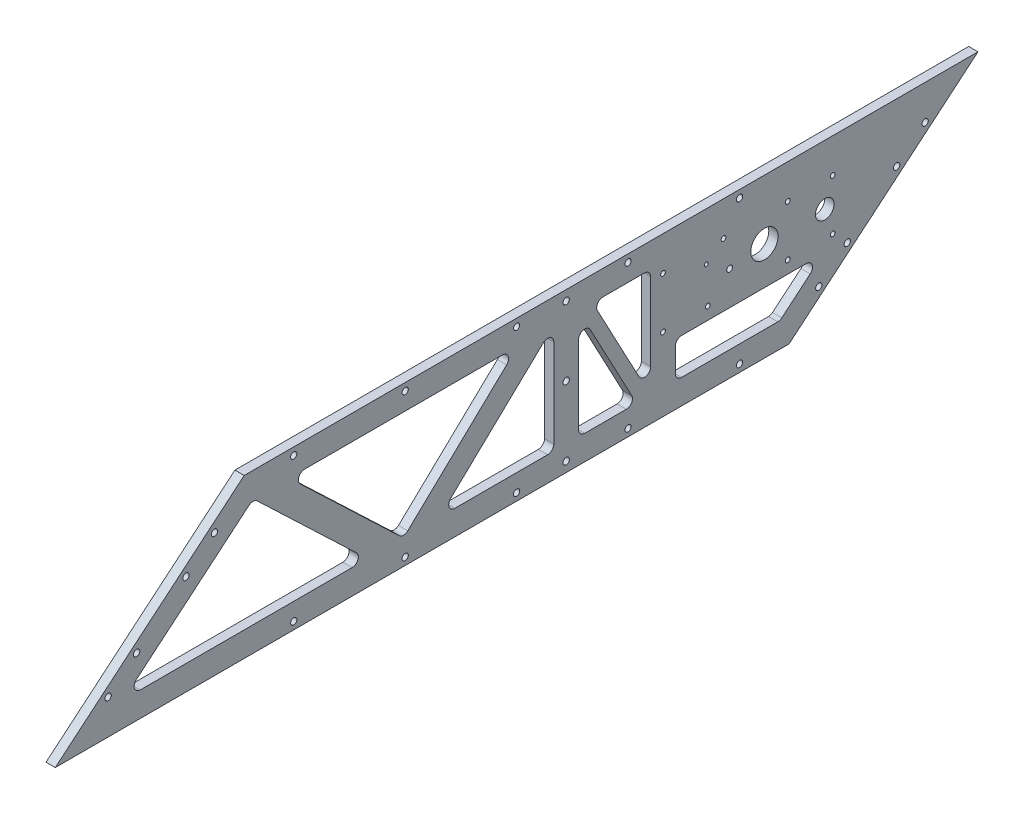
SolidWorks part; units mm, degrees
material "6061-T6 (SS)"
ref_plane "Front Plane" through (0, 0, 0) normal (0, 0, 1) x (1, 0, 0)
ref_plane "Top Plane" through (0, 0, 0) normal (0, 1, 0) x (1, 0, 0)
ref_plane "Right Plane" through (0, 0, 0) normal (1, 0, 0) x (0, 0, -1)
sketch "Sketch1" plane through (0, 0, 0) normal (1, 0, 0) x (0, 0, -1)
  line L0 (0, 12.7) -> (0, -12.7) construction
  line L1 (0, -12.7) -> (33.2976, -40.64) construction
  line L2 (33.2976, -40.64) -> (312.6976, -40.64)
  line L3 (312.6976, -40.64) -> (345.9952, -12.7)
  line L4 (345.9952, -12.7) -> (345.9952, 12.7) construction
  line L5 (345.9952, 12.7) -> (312.6976, 40.64) construction
  line L6 (312.6976, 40.64) -> (33.2976, 40.64)
  line L7 (33.2976, 40.64) -> (0, 12.7)
  line L8 (33.2976, 40.64) -> (33.2976, -40.64) construction
  line L9 (312.6976, 40.64) -> (312.6976, -40.64) construction
  line L10 (0, 0) -> (345.9952, 0) construction
  line L11 (0, 12.7) -> (-63.5681, -40.64)
  line L12 (-63.5681, -40.64) -> (33.2976, -40.64)
  line L13 (312.6976, 40.64) -> (409.5633, 40.64)
  line L14 (409.5633, 40.64) -> (345.9952, -12.7)
  point P10 (33.2976, 0)
  point P12 (312.6976, 0)
  dimension "D1" = 81.28
  dimension "D2" = 279.4
  dimension "D3" = 25.4
  dimension "D4" = 40
extrude "Boss-Extrude1" add sketch "Sketch1" along normal blind 4.7625
sketch "Sketch2" plane through (4.7625, 0, 0) normal (1, 0, 0) x (0, 0, -1)
  line L0 (-3.2177, 10) -> (373.048, 10) construction
  line L1 (312.6976, -40.64) -> (409.5633, 40.64) construction
  line L2 (345.048, 10) -> (245.048, 10) construction
  line L3 (245.048, -5) -> (345.048, -5) construction
  line L4 (245.048, -5) -> (245.048, 25) construction
  line L5 (245.048, 25) -> (345.048, 25) construction
  line L6 (345.048, -5) -> (345.048, 25) construction
  line L7 (0, 0) -> (361.1305, 0) construction
  line L9 (33.2976, 40.64) -> (-63.5681, -40.64) construction
  circle A0 centre (300.048, 10) radius 6.9977
  circle A1 centre (282.2147, 8) radius 1.4986
  circle A2 centre (270.2178, 15.9334) radius 0.9906
  circle A3 centre (282.2147, 8) radius 11.4777 construction
  circle A4 centre (270.2178, 15.9334) radius 7.1501 construction
  circle A5 centre (300.048, 10) radius 12.827 construction
  circle A6 centre (261.048, 10) radius 14 construction
  circle A7 centre (282.2147, 8) radius 5.1181 construction
  circle A8 centre (331.0042, 10) radius 4.7625
  point P11 (300.048, 10)
  point P12 (282.2147, 8)
  point P13 (270.2178, 15.9334)
  point P23 (261.048, 10)
  dimension "D5" = 13.9954
  dimension "D6" = 2.9972
  dimension "D7" = 1.9812
  dimension "D8" = 25.654
  dimension "D9" = 22.9553
  dimension "D10" = 14.3002
  dimension "D12" = 28
  dimension "D13" = 10.2362
  dimension "D17" = 9.525
  dimension "D1" = 17.9451
  dimension "D2" = 14.3828
  dimension "D3" = 30
  dimension "D4" = 100
  dimension "D11" = 10.922
  dimension "D14" = 16
  dimension "D15" = 13
  dimension "D16" = 55
  dimension "D18" = 30.9562
  dimension "D19" = 28
  dimension "D20" = 10
extrude "Gearbox (with Press fits)" cut sketch "Sketch2" against normal through all
sketch "Sketch6" plane through (4.7625, 0, 0) normal (1, 0, 0) x (0, 0, -1)
  line L0 (0, 0) -> (361.1305, 0) construction
  line L2 (28.757, 36.83) -> (405.0227, 36.83) construction
  line L3 (33.2976, 40.64) -> (-63.5681, -40.64) construction
  line L5 (409.5633, 40.64) -> (33.2976, 40.64) construction
  line L6 (312.6976, -40.64) -> (409.5633, 40.64) construction
  circle A0 centre (287.2976, 36.83) radius 1.5939
  circle A1 centre (230.1476, 36.83) radius 1.5939
  circle A2 centre (172.9976, 36.83) radius 1.5939
  circle A3 centre (115.8476, 36.83) radius 1.5938
  circle A4 centre (58.6976, 36.83) radius 1.5938
  circle A5 centre (58.6976, -36.83) radius 1.5938
  circle A6 centre (115.8476, -36.83) radius 1.5938
  circle A7 centre (172.9976, -36.83) radius 1.5939
  circle A8 centre (230.1476, -36.83) radius 1.5939
  circle A9 centre (287.2976, -36.83) radius 1.5939
  dimension "D2" = 3.1877
  dimension "D1" = 3.81
  dimension "D3" = 25.4
  dimension "D4" = 5
extrude "Cut-Extrude2" cut sketch "Sketch6" against normal through all
hole_wizard "#4 Clearance Hole2" positions "Sketch8" profile "Sketch7" hole size "#4" standard "ANSI Inch" end condition through all
sketch "Sketch8" plane through (4.7625, 0, 0) normal (1, 0, 0) x (0, 0, -1)
  line L0 (0, 0) -> (361.1305, 0) construction
  line L1 (312.6976, -40.64) -> (409.5633, 40.64) construction
  line L3 (27.2435, 35.56) -> (403.5092, 35.56) construction
  line L4 (33.2976, 40.64) -> (-63.5681, -40.64) construction
  line L7 (198.3976, 35.56) -> (198.3976, -35.56) construction
  line L8 (409.5633, 40.64) -> (33.2976, 40.64) construction
  point P15 (198.3976, 35.56)
  point P18 (198.3976, -35.56)
  point P30 (198.3976, 0)
  dimension "D2" = 165.1
  dimension "D3" = 5.08
sketch "Sketch7" plane through (4.7625, 35.56, -198.3976) normal (0, 1, 0) x (0, 0, -1)
  line L0 (0, 0) -> (0, 4.7625)
  line L1 (0, 4.7625) -> (1.6319, 4.7625)
  line L2 (1.6319, 4.7625) -> (1.6319, 0)
  line L5 (1.6319, 0) -> (0, 0)
  line L11 (0, -6.35) -> (0, 107.95) construction
  dimension "Thru Hole Dia." = 3.2639
  dimension "Thru Hole Depth" = 4.7625
hole_wizard "#2 Clearance Hole1" positions "Sketch10" profile "Sketch9" hole size "#2" standard "ANSI Inch"
sketch "Sketch10" plane through (4.7625, 0, 0) normal (1, 0, 0) x (0, 0, -1)
  line L0 (245.048, 40.64) -> (245.048, -40.64) construction
  line L1 (409.5633, 40.64) -> (33.2976, 40.64) construction
  line L2 (-63.5681, -40.64) -> (312.6976, -40.64) construction
  line L4 (248.048, 40.64) -> (248.048, -40.64) construction
  line L6 (245.048, 23) -> (335.048, 23) construction
  line L8 (245.048, -6) -> (328.5196, -6) construction
  line L10 (245.048, -3) -> (335.048, -3) construction
  line L11 (312.048, 23) -> (312.048, -3) construction
  line L12 (373.048, 10) -> (261.048, 10) construction
  line L13 (312.6976, -40.64) -> (409.5633, 40.64) construction
  line L14 (331.0042, 10) -> (331.0042, 40.64) construction
  line L15 (335.048, 23) -> (335.048, -3) construction
  circle A0 centre (331.0042, 10) radius 4.7625 construction
  point P25 (248.048, -3)
  point P27 (248.048, 23)
  point P29 (271.048, -3)
  point P31 (312.048, -3)
  point P33 (279.048, 23)
  point P35 (312.048, 23)
  point P70 (335.048, 23)
  point P72 (335.048, -3)
  dimension "D1" = 3
  dimension "D2" = 3
  dimension "D3" = 26
  dimension "D4" = 34
  dimension "D5" = 67
  dimension "D6" = 29
  dimension "D7" = 69.9562
  dimension "D8" = 16
  dimension "D9" = 16
  dimension "D10" = 90
sketch "Sketch9" plane through (4.7625, -3, -248.048) normal (0, 1, 0) x (0, 0, -1)
  line L0 (0, 0) -> (0, 5.5586)
  line L1 (0, 5.5586) -> (1.2192, 4.826)
  line L2 (1.2192, 4.826) -> (1.2192, 0)
  line L5 (1.2192, 0) -> (0, 0)
  line L10 (0, 5.5586) -> (-1.2192, 4.826) construction
  line L11 (0, -6.35) -> (0, 107.95) construction
  dimension "Hole Dia." = 2.4384
  dimension "Hole Depth" = 4.826
  dimension "Drill Angle" = 118
hole_wizard "#4 Clearance Hole1" positions "Sketch12" profile "Sketch11" hole size "#4" standard "ANSI Inch"
sketch "Sketch12" plane through (4.7625, 0, 0) normal (1, 0, 0) x (0, 0, -1)
  line L9 (-15.1353, 0) -> (361.1305, 0) construction
  line L10 (33.2976, 40.64) -> (-63.5681, -40.64) construction
  line L11 (312.6976, -40.64) -> (409.5633, 40.64) construction
  line L13 (403.636, 40.64) -> (306.7703, -40.64) construction
  line L14 (409.5633, 40.64) -> (33.2976, 40.64) construction
  line L15 (-63.5681, -40.64) -> (312.6976, -40.64) construction
  line L17 (39.2249, 40.64) -> (-57.6408, -40.64) construction
  line L18 (355.2032, 0) -> (-9.208, 0) construction
  line L19 (-36.4485, -22.8575) -> (327.9626, -22.8575) construction
  line L21 (-21.8554, -10.6124) -> (342.5558, -10.6124) construction
  line L23 (3.4394, 10.6124) -> (367.8505, 10.6124) construction
  line L25 (18.0326, 22.8575) -> (382.4437, 22.8575) construction
  point P40 (327.9626, -22.8575)
  point P42 (342.5558, -10.6124)
  point P44 (367.8505, 10.6124)
  point P46 (382.4437, 22.8575)
  point P54 (-36.4485, -22.8575)
  point P56 (-21.8554, -10.6124)
  point P58 (3.4394, 10.6124)
  point P60 (18.0326, 22.8575)
  dimension "D1" = 16.51
  dimension "D2" = 19.05
  dimension "D3" = 16.51
  dimension "D4" = 19.05
  dimension "D5" = 3.81
  dimension "D6" = 3.81
sketch "Sketch11" plane through (4.7625, -22.8575, -327.9626) normal (0, 1, 0) x (0, 0, -1)
  line L0 (0, 0) -> (0, 5.8066)
  line L1 (0, 5.8066) -> (1.6319, 4.826)
  line L2 (1.6319, 4.826) -> (1.6319, 0)
  line L5 (1.6319, 0) -> (0, 0)
  line L10 (0, 5.8066) -> (-1.6319, 4.826) construction
  line L11 (0, -6.35) -> (0, 107.95) construction
  dimension "Hole Dia." = 3.2639
  dimension "Hole Depth" = 4.826
  dimension "Drill Angle" = 118
sketch "Sketch15" plane through (4.7625, 0, 0) normal (1, 0, 0) x (0, 0, -1)
  line L0 (217.2296, 27.94) -> (238.523, 27.94)
  line L1 (210.725, 16.7148) -> (232.0185, -23.2727)
  line L2 (204.7476, -24.765) -> (204.7476, 15.2225)
  line L3 (-28.6752, -27.94) -> (37.92, 27.94) construction
  line L4 (214.4271, 23.2727) -> (235.7206, -16.7148)
  line L5 (241.698, 24.765) -> (241.698, -15.2225)
  line L6 (229.216, -27.94) -> (207.9226, -27.94)
  line L7 (-48.4329, -27.94) -> (327.8329, -27.94) construction
  line L8 (33.2976, 40.64) -> (-63.5681, -40.64) construction
  line L9 (312.6976, -40.64) -> (409.5633, 40.64) construction
  line L10 (-63.5681, -40.64) -> (312.6976, -40.64) construction
  line L11 (18.1623, 27.94) -> (394.4281, 27.94) construction
  line L12 (409.5633, 40.64) -> (33.2976, 40.64) construction
  line L13 (35.7449, 26.1148) -> (-21.9928, -22.3328)
  line L14 (-19.9519, -27.94) -> (88.637, -27.94)
  line L15 (90.8271, -22.4663) -> (39.9758, 25.9814)
  line L16 (62.0768, 22.4663) -> (112.7937, -25.8534)
  line L17 (117.1739, -25.8534) -> (167.8909, 22.4663)
  line L18 (64.2668, 27.94) -> (165.7008, 27.94)
  line L19 (139.1405, -22.4663) -> (186.6825, 22.8285)
  line L20 (192.0476, 20.5298) -> (192.0476, -24.765)
  line L21 (188.8726, -27.94) -> (141.3306, -27.94)
  line L22 (114.9838, 27.94) -> (114.9838, -27.94) construction
  line L23 (254.398, 27.94) -> (254.398, -27.94) construction
  line L24 (254.398, -12.525) -> (254.398, -24.765)
  line L25 (257.573, -27.94) -> (306.9196, -27.94)
  line L26 (308.9604, -27.1972) -> (323.5475, -14.9572)
  line L27 (321.5066, -9.35) -> (257.573, -9.35)
  circle A0 centre (198.3976, 0) radius 6.35 construction
  circle A1 centre (198.3976, 35.56) radius 6.35 construction
  circle A2 centre (198.3976, -35.56) radius 6.35 construction
  circle A3 centre (248.048, -3) radius 6.35 construction
  arc A4 (204.7476, -24.765) -> (207.9226, -27.94) centre (207.9226, -24.765) ccw
  arc A5 (229.216, -27.94) -> (232.0185, -23.2727) centre (229.216, -24.765) ccw
  arc A6 (241.698, -15.2225) -> (235.7206, -16.7148) centre (238.523, -15.2225) cw
  arc A7 (238.523, 27.94) -> (241.698, 24.765) centre (238.523, 24.765) cw
  arc A8 (217.2296, 27.94) -> (214.4271, 23.2727) centre (217.2296, 24.765) ccw
  arc A9 (204.7476, 15.2225) -> (210.725, 16.7148) centre (207.9226, 15.2225) cw
  arc A10 (-21.9928, -22.3328) -> (-19.9519, -27.94) centre (-19.9519, -24.765) ccw
  arc A11 (186.6825, 22.8285) -> (192.0476, 20.5298) centre (188.8726, 20.5298) cw
  arc A12 (192.0476, -24.765) -> (188.8726, -27.94) centre (188.8726, -24.765) cw
  arc A13 (139.1405, -22.4663) -> (141.3306, -27.94) centre (141.3306, -24.765) ccw
  arc A14 (88.637, -27.94) -> (90.8271, -22.4663) centre (88.637, -24.765) ccw
  arc A15 (35.7449, 26.1148) -> (39.9758, 25.9814) centre (37.7857, 23.6826) cw
  arc A16 (112.7937, -25.8534) -> (117.1739, -25.8534) centre (114.9838, -23.5547) ccw
  arc A17 (167.8909, 22.4663) -> (165.7008, 27.94) centre (165.7008, 24.765) ccw
  arc A18 (62.0768, 22.4663) -> (64.2668, 27.94) centre (64.2668, 24.765) cw
  circle A19 centre (271.048, -3) radius 6.35 construction
  arc A20 (323.5475, -14.9572) -> (321.5066, -9.35) centre (321.5066, -12.525) ccw
  arc A21 (306.9196, -27.94) -> (308.9604, -27.1972) centre (306.9196, -24.765) ccw
  arc A22 (254.398, -24.765) -> (257.573, -27.94) centre (257.573, -24.765) ccw
  arc A23 (254.398, -12.525) -> (257.573, -9.35) centre (257.573, -12.525) cw
  point P15 (204.7476, -27.94)
  point P36 (241.698, -27.94)
  point P40 (204.7476, -27.94)
  point P59 (192.0476, 27.94)
  point P62 (192.0476, -27.94)
  point P65 (133.3952, -27.94)
  point P68 (96.5724, -27.94)
  point P77 (173.6362, 27.94)
  point P80 (56.3315, 27.94)
  point P82 (204.7476, 27.94)
  point P95 (308.0752, -27.94)
  point P101 (254.398, -9.35)
  dimension "D1" = 12.7
  dimension "D2" = 12.7
  dimension "D3" = 12.7
  dimension "D4" = 12.7
  dimension "D8" = 3.175
  dimension "D12" = 3.175
  dimension "D13" = 12.7
  dimension "D15" = 3.175
  dimension "D5" = 12.7
  dimension "D6" = 12.7
  dimension "D7" = 6.35
  dimension "D9" = 12.7
  dimension "D10" = 12.7
  dimension "D11" = 12.7
  dimension "D14" = 12.7
extrude "Cut-Extrude3" cut sketch "Sketch15" against normal through all
